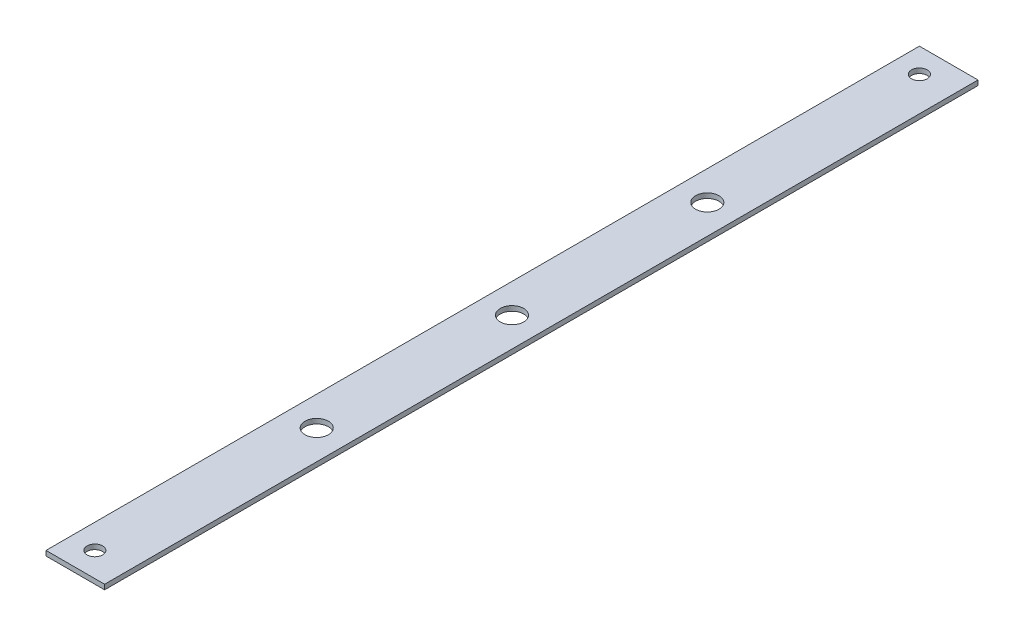
SolidWorks part; units mm, degrees
ref_plane "Front Plane" through (0, 0, 0) normal (0, 0, 1) x (1, 0, 0)
ref_plane "Top Plane" through (0, 0, 0) normal (0, 1, 0) x (1, 0, 0)
ref_plane "Right Plane" through (0, 0, 0) normal (1, 0, 0) x (0, 0, -1)
sketch "Sketch1" plane through (0, 0, 0) normal (0, 0, 1) x (1, 0, 0)
  line L0 (2.5, 2.5) -> (0, 2.5)
  line L1 (0, 2.5) -> (0, 0)
  line L3 (2.5, 2.5) -> (30, 2.5)
  line L4 (30, 2.5) -> (30, 0)
  line L5 (30, 0) -> (0, 0)
  dimension "D2" = 2.5
  dimension "D4" = 30
extrude "Boss-Extrude1" add sketch "Sketch1" along normal mid plane 447.2
sketch "Sketch2" plane through (0, 2.5, 0) normal (0, 1, 0) x (1, 0, 0)
  line L0 (30, -223.6) -> (0, -223.6) construction
  line L2 (30, -223.6) -> (30, 223.6) construction
  line L3 (0, 223.6) -> (30, 223.6) construction
  line L8 (0, -223.6) -> (30, -223.6) construction
  line L9 (30, -223.6) -> (30, 223.6) construction
  line L10 (0, 223.6) -> (30, 223.6) construction
  circle A0 centre (12.5, 211.1) radius 4
  circle A1 centre (12.5, -211.1) radius 4
  circle A2 centre (15, -100) radius 6
  circle A3 centre (15, 100) radius 6
  circle A4 centre (15, 0) radius 6
  point P9 (15, 223.6)
  point P22 (30, 0)
  dimension "D2" = 8
  dimension "D6" = 12.5
  dimension "D10" = 12
  dimension "D11" = 12
  dimension "D12" = 12
  dimension "D3" = 17.5
  dimension "D4" = 12.5
  dimension "D5" = 223.6
  dimension "D7" = 15
  dimension "D8" = 100
  dimension "D9" = 100
  dimension "D13" = 15
  dimension "D14" = 17.5
  dimension "D15" = 223.6
extrude "Cut-Extrude1" cut sketch "Sketch2" against normal through all
